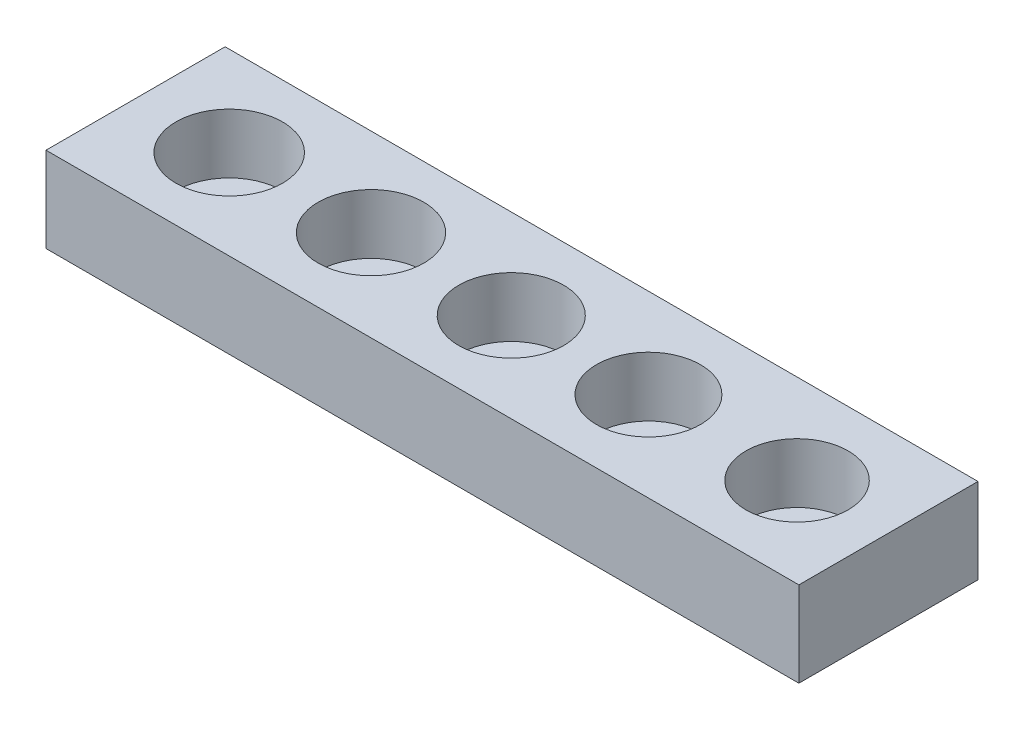
SolidWorks part; units mm, degrees
ref_plane "Front Plane" through (0, 0, 0) normal (0, 0, 1) x (1, 0, 0)
ref_plane "Top Plane" through (0, 0, 0) normal (0, 1, 0) x (1, 0, 0)
ref_plane "Right Plane" through (0, 0, 0) normal (1, 0, 0) x (0, 0, -1)
sketch "Sketch4" plane through (0, 0, 0) normal (0, 1, 0) x (1, 0, 0)
  line L1 (-22.0919, -5.2558) -> (22.0919, -5.2558)
  line L2 (-22.0919, -5.2558) -> (-22.0919, 5.2558)
  line L3 (-22.0919, 5.2558) -> (22.0919, 5.2558)
  line L4 (22.0919, -5.2558) -> (22.0919, 5.2558)
  line L5 (-22.0919, -5.2558) -> (22.0919, 5.2558) construction
  line L6 (-22.0919, 5.2558) -> (22.0919, -5.2558) construction
  point P0 (0, 0)
extrude "Boss-Extrude1" add sketch "Sketch4" along normal blind 5 contours L2 L1 L4 L3
sketch "Sketch5" plane through (0, 5, 0) normal (0, 1, 0) x (1, 0, 0)
  line L0 (-22.0919, 0) -> (22.0919, 0) construction
  line L1 (-22.0919, -5.2558) -> (-22.0919, 5.2558) construction
  line L2 (22.0919, -5.2558) -> (22.0919, 5.2558) construction
  circle A0 centre (-16.5954, 0) radius 3.125
  circle A1 centre (-8.3637, 0.089) radius 3.1
  circle A2 centre (-0.0445, 0) radius 3.075
  circle A3 centre (8.0078, 0) radius 3.05
  circle A4 centre (16.7275, 0) radius 3
extrude "Cut-Extrude1" cut sketch "Sketch5" against normal blind 3.5
